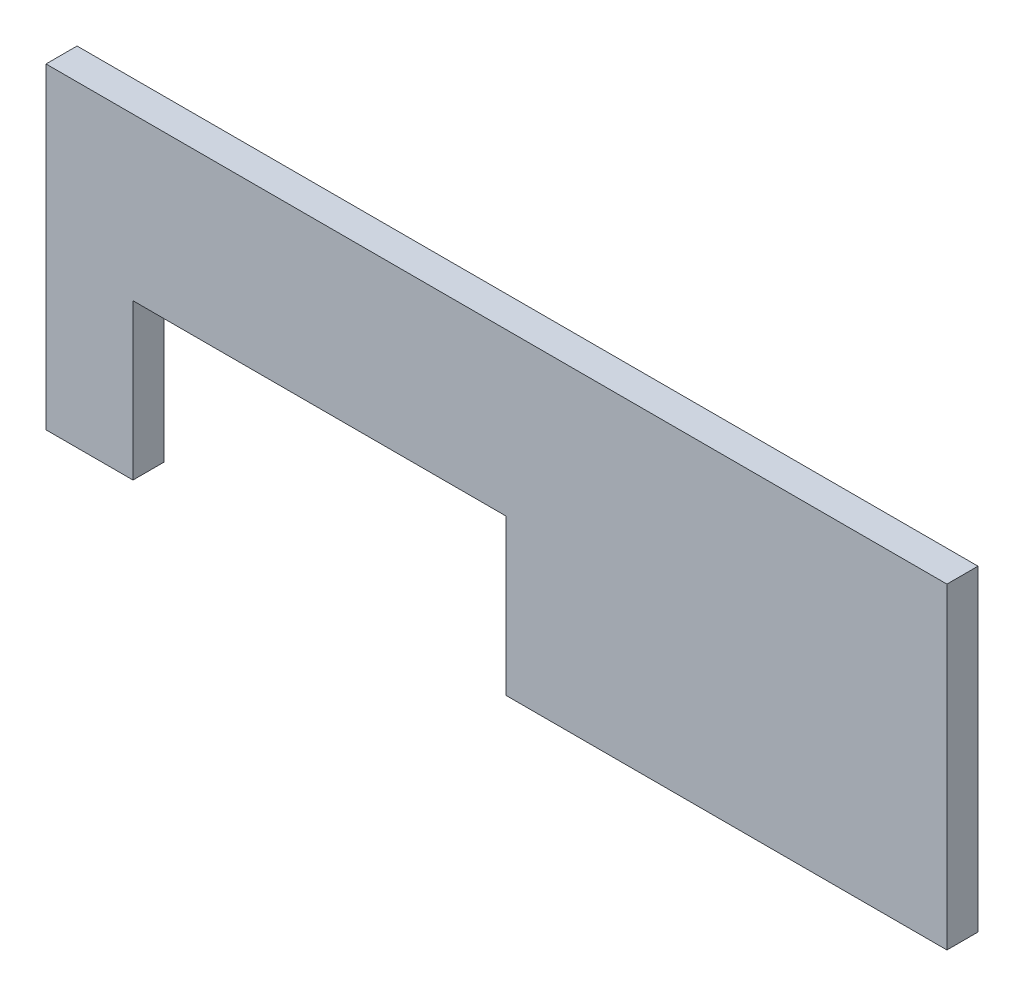
SolidWorks part; units mm, degrees
ref_plane "Plan de face" through (0, 0, 0) normal (0, 0, 1) x (1, 0, 0)
ref_plane "Plan de dessus" through (0, 0, 0) normal (0, 1, 0) x (1, 0, 0)
ref_plane "Plan de droite" through (0, 0, 0) normal (1, 0, 0) x (0, 0, -1)
sketch "Esquisse1" plane through (0, 0, 0) normal (0, 0, 1) x (1, 0, 0)
  line L0 (-48.7494, -48.1623) -> (-34.7494, -48.1623)
  line L1 (-48.7494, 2.8377) -> (96.2506, 2.8377)
  line L2 (-48.7494, 2.8377) -> (-48.7494, -48.1623)
  line L3 (-34.7494, -48.1623) -> (-34.7494, -23.1623)
  line L4 (96.2506, 2.8377) -> (96.2506, -48.1623)
  line L5 (-34.7494, -23.1623) -> (25.2506, -23.1623)
  line L6 (25.2506, -23.1623) -> (25.2506, -48.1623)
  line L7 (25.2506, -48.1623) -> (96.2506, -48.1623)
  dimension "D1" = 51
  dimension "D2" = 145
  dimension "D3" = 14
  dimension "D4" = 60
  dimension "D5" = 25
extrude "Extrusion1" add sketch "Esquisse1" along normal blind 5
